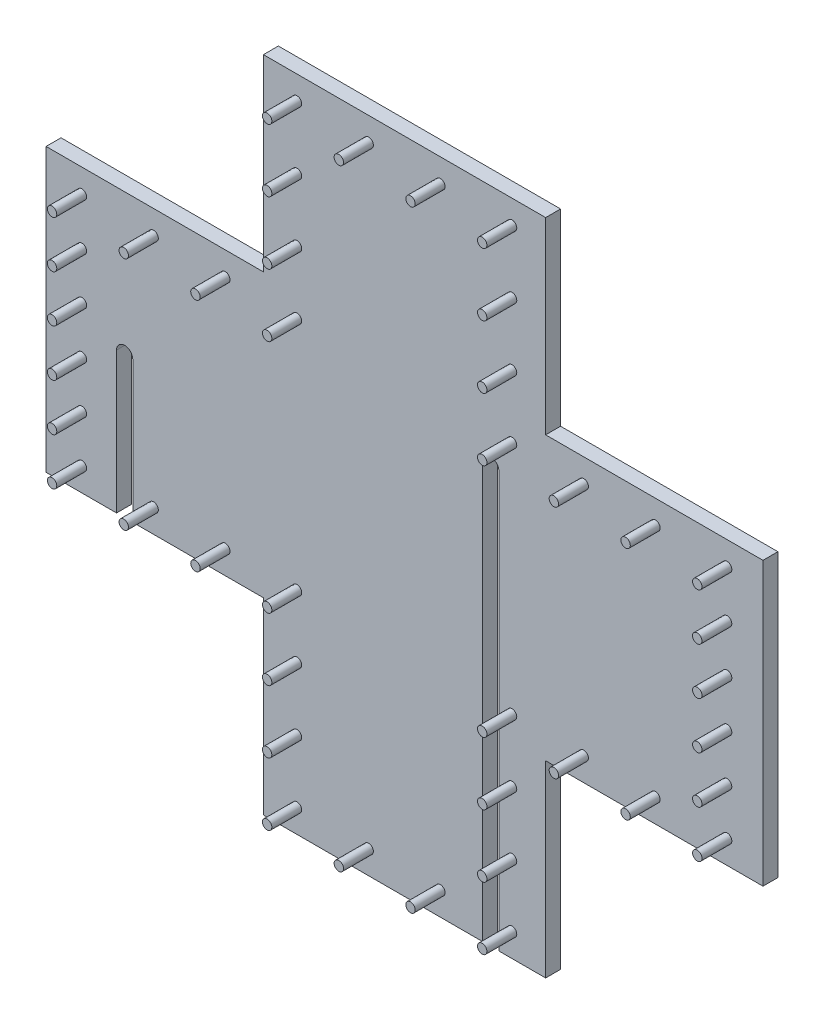
SolidWorks part; units mm, degrees
ref_plane "Front Plane" through (0, 0, 0) normal (0, 0, 1) x (1, 0, 0)
ref_plane "Top Plane" through (0, 0, 0) normal (0, 1, 0) x (1, 0, 0)
ref_plane "Right Plane" through (0, 0, 0) normal (1, 0, 0) x (0, 0, -1)
sketch "Sketch1" plane through (0, 0, 0) normal (0, 0, 1) x (1, 0, 0)
  line L1 (0, 0) -> (152.4, 0)
  line L2 (0, 0) -> (0, -152.4)
  line L3 (0, -152.4) -> (152.4, -152.4)
  line L4 (152.4, 0) -> (152.4, -152.4)
  circle A0 centre (12.7, -12.7) radius 6.342 construction
  circle A1 centre (94.5382, -57.8618) radius 1.725
  circle A2 centre (94.5382, -94.5382) radius 1.725
  circle A3 centre (16.7, -76.2) radius 1.725
  circle A4 centre (139.7, -76.2) radius 6.342 construction
  circle A5 centre (12.7, -139.7) radius 6.342 construction
  circle A8 centre (38.1, -12.7) radius 3.2639
  circle A9 centre (12.7, -38.1) radius 3.2639
  circle A10 centre (114.3, -12.7) radius 3.2639
  circle A11 centre (139.7, -38.1) radius 3.2639
  circle A12 centre (139.7, -114.3) radius 3.2639
  circle A13 centre (114.3, -139.7) radius 3.2639
  circle A14 centre (38.1, -139.7) radius 3.2639
  circle A15 centre (12.7, -114.3) radius 3.2639
  dimension "D1" = 3.45
sketch "Sketch2" plane through (0, 0, 0) normal (0, 0, 1) x (1, 0, 0)
  line L0 (0, 0) -> (0, -152.4) construction
  line L1 (0, -46.2) -> (152.4, -46.2)
  line L2 (0, -46.2) -> (0, -106.2)
  line L3 (0, -106.2) -> (152.4, -106.2)
  line L4 (152.4, -46.2) -> (152.4, -106.2)
  line L5 (152.4, 0) -> (152.4, -152.4) construction
  line L6 (46.2, -46.2) -> (46.2, -6.2)
  line L7 (46.2, -6.2) -> (106.2, -6.2)
  line L8 (106.2, -6.2) -> (106.2, -46.2)
  line L9 (46.2, -106.2) -> (46.2, -146.2)
  line L10 (46.2, -146.2) -> (106.2, -146.2)
  line L11 (106.2, -146.2) -> (106.2, -106.2)
  line L12 (53.34, -101.2) -> (53.34, -114.5333) construction
  line L13 (53.34, -114.5333) -> (53.34, -127.8667) construction
  line L14 (53.34, -127.8667) -> (53.34, -141.2) construction
  line L15 (53.34, -141.2) -> (68.58, -141.2) construction
  line L16 (68.58, -141.2) -> (83.82, -141.2) construction
  line L17 (83.82, -141.2) -> (99.06, -141.2) construction
  line L18 (99.06, -141.2) -> (99.06, -127.8667) construction
  line L19 (99.06, -127.8667) -> (99.06, -114.5333) construction
  line L20 (99.06, -114.5333) -> (99.06, -101.2) construction
  line L21 (0, -76.2) -> (152.4, -76.2) construction
  circle A0 centre (7.62, -101.2) radius 1
  circle A1 centre (22.86, -101.2) radius 1
  circle A2 centre (38.1, -101.2) radius 1
  circle A3 centre (53.34, -101.2) radius 1
  circle A4 centre (68.58, -101.2) radius 1
  circle A5 centre (83.82, -101.2) radius 1
  circle A6 centre (99.06, -101.2) radius 1
  circle A7 centre (114.3, -101.2) radius 1
  circle A8 centre (129.54, -101.2) radius 1
  circle A9 centre (144.78, -101.2) radius 1
  circle A10 centre (53.34, -114.5333) radius 1
  circle A11 centre (53.34, -127.8667) radius 1
  circle A12 centre (53.34, -141.2) radius 1
  circle A13 centre (68.58, -141.2) radius 1
  circle A14 centre (83.82, -141.2) radius 1
  circle A15 centre (99.06, -141.2) radius 1
  circle A16 centre (99.06, -127.8667) radius 1
  circle A17 centre (99.06, -114.5333) radius 1
  circle A18 centre (7.62, -91.2) radius 1
  circle A19 centre (7.62, -81.2) radius 1
  circle A20 centre (144.78, -91.2) radius 1
  circle A21 centre (144.78, -81.2) radius 1
  circle A22 centre (144.78, -71.2) radius 1
  circle A23 centre (144.78, -61.2) radius 1
  circle A24 centre (144.78, -51.2) radius 1
  circle A25 centre (129.54, -51.2) radius 1
  circle A26 centre (114.3, -51.2) radius 1
  circle A27 centre (99.06, -51.2) radius 1
  circle A28 centre (99.06, -37.8667) radius 1
  circle A29 centre (99.06, -24.5333) radius 1
  circle A30 centre (99.06, -11.2) radius 1
  circle A31 centre (83.82, -11.2) radius 1
  circle A32 centre (68.58, -11.2) radius 1
  circle A33 centre (53.34, -11.2) radius 1
  circle A34 centre (53.34, -24.5333) radius 1
  circle A35 centre (53.34, -37.8667) radius 1
  circle A36 centre (53.34, -51.2) radius 1
  circle A37 centre (38.1, -51.2) radius 1
  circle A38 centre (22.86, -51.2) radius 1
  circle A39 centre (7.62, -51.2) radius 1
  circle A40 centre (7.62, -61.2) radius 1
  circle A41 centre (7.62, -71.2) radius 1
  point P17 (0, -76.2)
  point P20 (76.2, -6.2)
  point P21 (76.2, -46.2)
  dimension "D4" = 2
  dimension "D1" = 60
  dimension "D2" = 40
  dimension "D3" = 60
  dimension "D5" = 5
  dimension "D6" = 7.62
  dimension "D7" = 152.4
  dimension "D9" = 7.62
  dimension "D10" = 5
  dimension "D12" = 10
  dimension "D8" = 10
  dimension "D11" = 3
  dimension "D13" = 3
extrude "Boss-Extrude1" add sketch "Sketch2" along normal mid plane 3.175 contours L8 L7 L6 L1 A34 A32 A30 A28 A29 A31 A33 A35 | L4 L1 L2 L3 A40 A38 A36 A26 A24 A22 A21 A20 A19 A18 A9 A8 A7 A6 A5 A4 A3 A2 A1 A0 A23 | L10 L11 L3 L9 A17 A16 A15 A14 A13 A12 A11 A10 | A0 | A18 | A19 | A1 | A2 | A3 | A11 | A12 | A13 | A14 | A15 | A16 | A17 | A6 | A5 | A4 | A7 | A9 | A20 | A21 | A22 | A24 | A23 | A25 | A26 | A27 | A28 | A29 | A30 | A31 | A32 | A33 | A34 | A35 | A36 | A37 | A38 | A39 | A40 | A41 | A8
sketch "Sketch3" plane through (0, 0, 0) normal (0, 0, 1) x (1, 0, 0)
  line L0 (16.7, -76.2) -> (16.7, -109.7942) construction
  line L1 (18.425, -76.2) -> (18.425, -109.7942)
  line L2 (14.975, -76.2) -> (14.975, -109.7942)
  line L3 (94.5382, -57.8618) -> (94.5382, -157.3522) construction
  line L4 (96.2632, -57.8618) -> (96.2632, -157.3522)
  line L5 (92.8132, -57.8618) -> (92.8132, -157.3522)
  arc A0 (18.425, -76.2) -> (14.975, -76.2) centre (16.7, -76.2) ccw
  arc A1 (14.975, -109.7942) -> (18.425, -109.7942) centre (16.7, -109.7942) ccw
  arc A2 (96.2632, -57.8618) -> (92.8132, -57.8618) centre (94.5382, -57.8618) ccw
  arc A3 (92.8132, -157.3522) -> (96.2632, -157.3522) centre (94.5382, -157.3522) ccw
  circle A4 centre (94.5382, -57.8618) radius 1.725 construction
  circle A5 centre (16.7, -76.2) radius 1.725 construction
  point P3 (16.7, -92.9971)
  point P8 (94.5382, -107.607)
sketch "Sketch4" plane through (0, 0, 0) normal (0, 0, 1) x (1, 0, 0)
  line L1 (0, -46.2) -> (152.4, -46.2)
  line L2 (0, -46.2) -> (0, -106.2)
  line L3 (0, -106.2) -> (152.4, -106.2)
  line L4 (152.4, -46.2) -> (152.4, -106.2)
  line L6 (46.2, -46.2) -> (46.2, -6.2)
  line L7 (46.2, -6.2) -> (106.2, -6.2)
  line L8 (106.2, -6.2) -> (106.2, -46.2)
  line L9 (46.2, -106.2) -> (46.2, -146.2)
  line L10 (46.2, -146.2) -> (106.2, -146.2)
  line L11 (106.2, -146.2) -> (106.2, -106.2)
  line L12 (53.34, -101.2) -> (53.34, -114.5333) construction
  line L13 (53.34, -114.5333) -> (53.34, -127.8667) construction
  line L14 (53.34, -127.8667) -> (53.34, -141.2) construction
  line L15 (53.34, -141.2) -> (68.58, -141.2) construction
  line L16 (68.58, -141.2) -> (83.82, -141.2) construction
  line L17 (83.82, -141.2) -> (99.06, -141.2) construction
  line L18 (99.06, -141.2) -> (99.06, -127.8667) construction
  line L19 (99.06, -127.8667) -> (99.06, -114.5333) construction
  line L20 (99.06, -114.5333) -> (99.06, -101.2) construction
  line L21 (0, -76.2) -> (152.4, -76.2) construction
  circle A0 centre (7.62, -101.2) radius 1
  circle A1 centre (22.86, -101.2) radius 1
  circle A2 centre (38.1, -101.2) radius 1
  circle A3 centre (53.34, -101.2) radius 1
  circle A4 centre (68.58, -101.2) radius 1
  circle A5 centre (83.82, -101.2) radius 1
  circle A6 centre (99.06, -101.2) radius 1
  circle A7 centre (114.3, -101.2) radius 1
  circle A8 centre (129.54, -101.2) radius 1
  circle A9 centre (144.78, -101.2) radius 1
  circle A10 centre (53.34, -114.5333) radius 1
  circle A11 centre (53.34, -127.8667) radius 1
  circle A12 centre (53.34, -141.2) radius 1
  circle A13 centre (68.58, -141.2) radius 1
  circle A14 centre (83.82, -141.2) radius 1
  circle A15 centre (99.06, -141.2) radius 1
  circle A16 centre (99.06, -127.8667) radius 1
  circle A17 centre (99.06, -114.5333) radius 1
  circle A18 centre (7.62, -91.2) radius 1
  circle A19 centre (7.62, -81.2) radius 1
  circle A20 centre (144.78, -91.2) radius 1
  circle A21 centre (144.78, -81.2) radius 1
  circle A22 centre (144.78, -71.2) radius 1
  circle A23 centre (144.78, -61.2) radius 1
  circle A24 centre (144.78, -51.2) radius 1
  circle A25 centre (129.54, -51.2) radius 1
  circle A26 centre (114.3, -51.2) radius 1
  circle A27 centre (99.06, -51.2) radius 1
  circle A28 centre (99.06, -37.8667) radius 1
  circle A29 centre (99.06, -24.5333) radius 1
  circle A30 centre (99.06, -11.2) radius 1
  circle A31 centre (83.82, -11.2) radius 1
  circle A32 centre (68.58, -11.2) radius 1
  circle A33 centre (53.34, -11.2) radius 1
  circle A34 centre (53.34, -24.5333) radius 1
  circle A35 centre (53.34, -37.8667) radius 1
  circle A36 centre (53.34, -51.2) radius 1
  circle A37 centre (38.1, -51.2) radius 1
  circle A38 centre (22.86, -51.2) radius 1
  circle A39 centre (7.62, -51.2) radius 1
  circle A40 centre (7.62, -61.2) radius 1
  circle A41 centre (7.62, -71.2) radius 1
  point P17 (0, -76.2)
  point P20 (76.2, -6.2)
  point P21 (76.2, -46.2)
  dimension "D4" = 2
  dimension "D1" = 60
  dimension "D2" = 40
  dimension "D3" = 60
  dimension "D5" = 5
  dimension "D6" = 7.62
  dimension "D7" = 152.4
  dimension "D9" = 7.62
  dimension "D10" = 5
  dimension "D12" = 10
  dimension "D8" = 10
  dimension "D11" = 3
  dimension "D13" = 3
extrude "Boss-Extrude2" add sketch "Sketch4" along normal blind 6.35 from surface at 1.5875 contours A33 | A32 | A30 | A31 | A29 | A28 | A26 | A27 | A24 | A25 | A23 | A22 | A21 | A20 | A9 | A7 | A8 | A6 | A17 | A16 | A15 | A14 | A13 | A12 | A11 | A10 | A3 | A2 | A0 | A1 | A18 | A19 | A41 | A39 | A40 | A38 | A36 | A37 | A35 | A34 starting at face at (76.2, -76.2, 1.5875)
extrude "Cut-Extrude1" cut sketch "Sketch3" against normal through all both and the other way through all
equation "\"D9@Sketch2\"=\"D6@Sketch2\""
